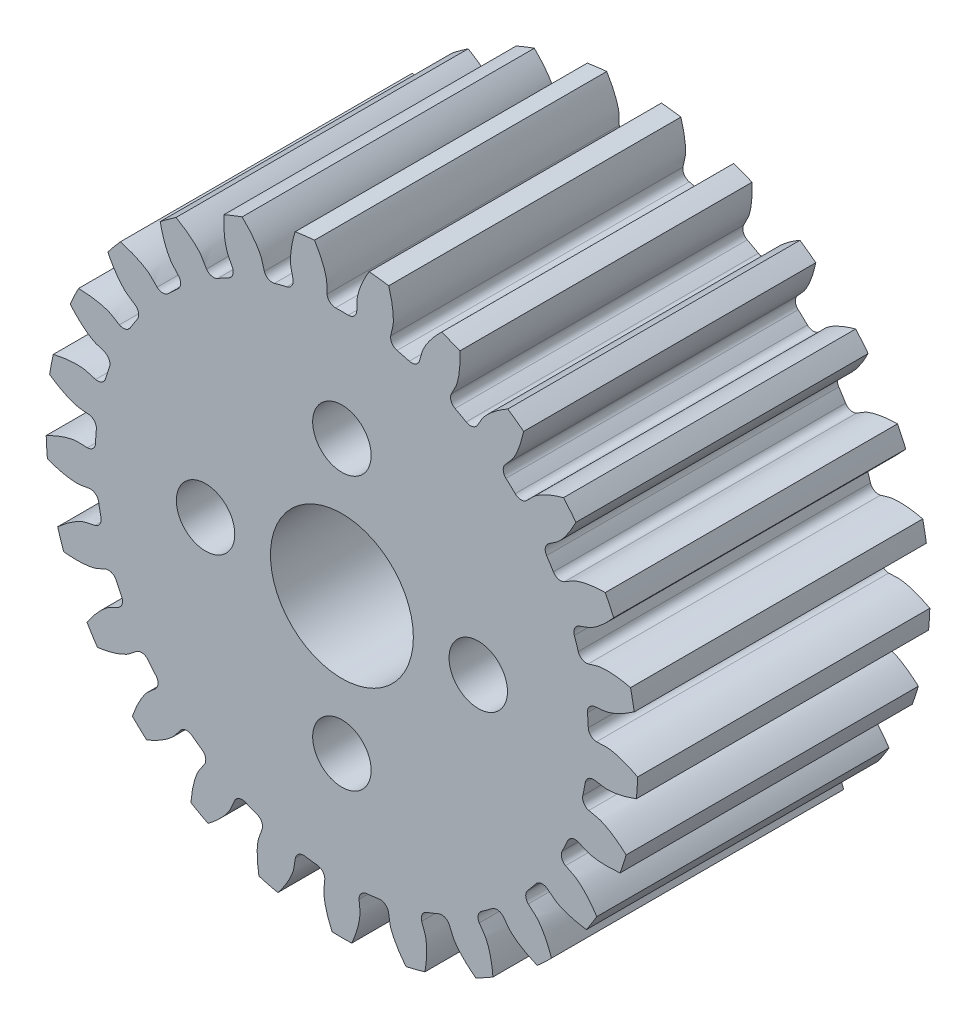
SolidWorks part; units mm, degrees
ref_plane "Front Plane" through (0, 0, 0) normal (0, 0, 1) x (1, 0, 0)
ref_plane "Top Plane" through (0, 0, 0) normal (0, 1, 0) x (1, 0, 0)
ref_plane "Right Plane" through (0, 0, 0) normal (1, 0, 0) x (0, 0, -1)
ref_axis "Axis1" through (0, 0, -88.99) along (0, 0, 1)
sketch "草图1" plane through (0, 0, 0) normal (0, 0, 1) x (1, 0, 0)
  circle A0 centre (0, 0) radius 15.1875
extrude "LaShenA" add sketch "草图1" along normal blind 15
sketch "SketchA" plane through (0, 0, 15) normal (0, 0, 1) x (1, 0, 0)
  line L0 (0, 0) -> (0, 15.1875) construction
  arc A0 (0.3244, 12.6521) -> (-0.3244, 12.6521) centre (0, 0) ccw
  arc A1 (1.842, 15.7559) -> (-1.842, 15.7559) centre (0, 0) ccw
  arc A2 (-0.3244, 12.6521) -> (-0.7617, 13.0474) centre (-0.3354, 13.0795) cw
  arc A3 (0.7617, 13.0474) -> (0.3244, 12.6521) centre (0.3354, 13.0795) cw
  circle A4 centre (0, 0) radius 13.6146 construction
  circle A5 centre (0, 0) radius 15.1875 construction
  circle A6 centre (0, 0) radius 12.6562 construction
  circle A7 centre (0, 0) radius 14.0625 construction
  spline S0 degree 3 poles (0.7617, 13.0474) (0.7753, 13.2289) (0.7594, 13.4417) (0.7888, 13.6649) (0.7997, 13.7227) (0.8093, 13.7685) (0.8217, 13.8211) (0.837, 13.8804) (0.8557, 13.9462) (0.878, 14.0185) (0.9042, 14.097) (0.9347, 14.1818) (0.9697, 14.2725) (1.0095, 14.369) (1.0545, 14.4712) (1.1048, 14.5789) (1.1608, 14.6918) (1.2227, 14.8098) (1.2907, 14.9327) (1.3653, 15.0601) (1.4465, 15.192) (1.5346, 15.328) (1.6644, 15.5184) (1.7689, 15.6607) (1.842, 15.7559) knots 0.123706 0.123706 0.123706 0.123706 0.284027 0.310496 0.322147 0.335916 0.351803 0.369808 0.389932 0.412174 0.436535 0.463013 0.49161 0.522325 0.555159 0.590111 0.627181 0.666369 0.707676 0.751101 0.796644 0.844306 0.894085 1 1 1 1
  spline S1 degree 3 poles (-0.7617, 13.0474) (-0.7753, 13.2289) (-0.7594, 13.4417) (-0.7888, 13.6649) (-0.7997, 13.7227) (-0.8093, 13.7685) (-0.8217, 13.8211) (-0.837, 13.8804) (-0.8557, 13.9462) (-0.878, 14.0185) (-0.9042, 14.097) (-0.9347, 14.1818) (-0.9697, 14.2725) (-1.0095, 14.369) (-1.0545, 14.4712) (-1.1048, 14.5789) (-1.1608, 14.6918) (-1.2227, 14.8098) (-1.2907, 14.9327) (-1.3653, 15.0601) (-1.4465, 15.192) (-1.5346, 15.328) (-1.6644, 15.5184) (-1.7689, 15.6607) (-1.842, 15.7559) knots 0.123706 0.123706 0.123706 0.123706 0.284027 0.310496 0.322147 0.335916 0.351803 0.369808 0.389932 0.412174 0.436535 0.463013 0.49161 0.522325 0.555159 0.590111 0.627181 0.666369 0.707676 0.751101 0.796644 0.844306 0.894085 1 1 1 1
  dimension "D1" = 0.4275
  dimension "Db" = 27.2292
  dimension "Da" = 30.375
  dimension "Df" = 25.3125
  dimension "Dn" = 28.125
extrude "Cut-ExtrudeA" cut sketch "SketchA" against normal blind 15
pattern_circular "www.KYTool.cn" count 25 over 360 about axis through (0, 0, -88.99) along (0, 0, 1) of "Cut-ExtrudeA"
sketch "草图2" plane through (0, 0, 15) normal (0, 0, 1) x (1, 0, 0)
  circle A0 centre (0, 0) radius 7 construction
  circle A1 centre (7, 0) radius 1.5
  circle A2 centre (0, -7) radius 1.5
  circle A3 centre (-7, 0) radius 1.5
  circle A4 centre (0, 7) radius 1.5
  point P14 (0, 0)
  dimension "D1" = 3
  dimension "D3" = 14
  dimension "D2" = 4
extrude "切除-拉伸1" cut sketch "草图2" against normal through all
sketch "草图3" plane through (0, 0, 0) normal (0, 0, -1) x (-1, 0, 0)
  circle A0 centre (0, 0) radius 10.1
  dimension "D1" = 20.2
extrude "切除-拉伸2" cut sketch "草图3" against normal blind 5
sketch "草图4" plane through (0, 0, 15) normal (0, 0, 1) x (1, 0, 0)
  circle A0 centre (0, 0) radius 3.6688
extrude "切除-拉伸3" cut sketch "草图4" against normal blind 10
